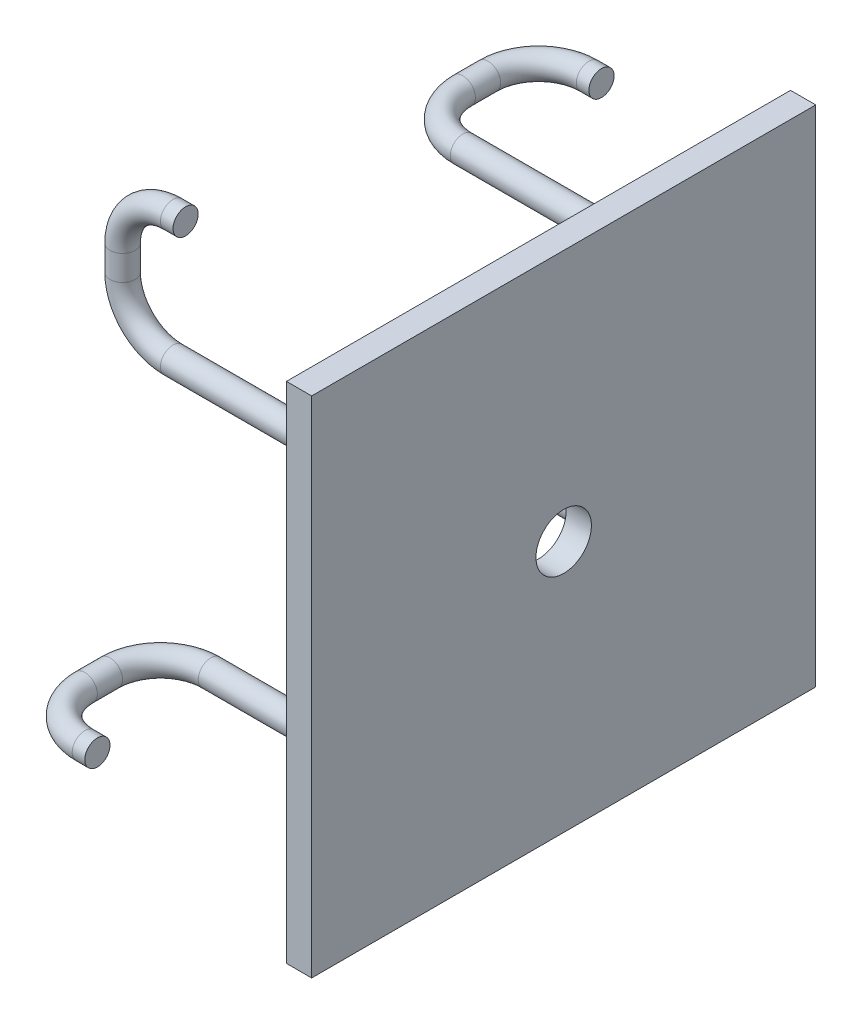
SolidWorks part; units mm, degrees
ref_plane "Front Plane" through (0, 0, 0) normal (0, 0, 1) x (1, 0, 0)
ref_plane "Top Plane" through (0, 0, 0) normal (0, 1, 0) x (1, 0, 0)
ref_plane "Right Plane" through (0, 0, 0) normal (1, 0, 0) x (0, 0, -1)
sketch "Sketch1" plane through (-450, 0, 0) normal (1, 0, 0) x (0, 0, -1)
  line L0 (112, 23410.1886) -> (112, 23210.1886) construction
  line L1 (212, 23410.1886) -> (12, 23410.1886)
  line L2 (212, 23410.1886) -> (212, 23210.1886)
  line L3 (212, 23210.1886) -> (12, 23210.1886)
  line L4 (12, 23410.1886) -> (12, 23210.1886)
  line L5 (212, 23310.1886) -> (12, 23310.1886) construction
  circle A0 centre (112, 23310.1886) radius 11 construction
  circle A1 centre (112, 23310.1886) radius 11
  point P8 (112, 23310.1886)
  dimension "D1" = 200
  dimension "D2" = 100
  dimension "D3" = 200
extrude "Boss-Extrude1" add sketch "Sketch1" against normal blind 10
sketch "Sketch3" plane through (-460, 0, 0) normal (-1, 0, 0) x (0, 0, 1)
  line L0 (-112, 23210.1886) -> (-112, 23310.1886) construction
  line L1 (-112, 23310.1886) -> (-225.1197, 23310.1886) construction
  line L2 (-12, 23210.1886) -> (-212, 23210.1886) construction
  line L3 (-212, 23210.1886) -> (-212, 23410.1886) construction
  circle A0 centre (-177, 23260.1886) radius 5
  circle A1 centre (-112, 23310.1886) radius 11 construction
  dimension "D1" = 10
  dimension "D3" = 35
  dimension "D2" = 50
sketch3d "3DSketch1"
  line L0 (-460, 23260.1886, -177) -> (-540, 23260.1886, -177)
  line L1 (-560, 23240.1886, -177) -> (-560, 23230.1886, -177)
  line L2 (-540, 23210.1886, -177) -> (-535, 23210.1886, -177)
  arc A0 (-540, 23260.1886, -177) -> (-560, 23240.1886, -177) centre (-540, 23240.1886, -177) ccw
  arc A1 (-560, 23230.1886, -177) -> (-540, 23210.1886, -177) centre (-540, 23230.1886, -177) ccw
  point P7 (-560, 23260.1886, -177)
  point P8 (-540, 23240.1886, -157)
  point P11 (-560, 23210.1886, -177)
  point P12 (-540, 23230.1886, -157)
  dimension "D1" = 20
  dimension "D2" = 100
  dimension "D5" = 20
  dimension "D3" = 50
  dimension "D4" = 25
sweep "Sweep1" add profiles "Sketch3" path "3DSketch1"
pattern_circular "CirPattern1" count 4 over 360 about axis through (0, 23310.1886, -112) along (1, 0, 0) of "Sweep1"
